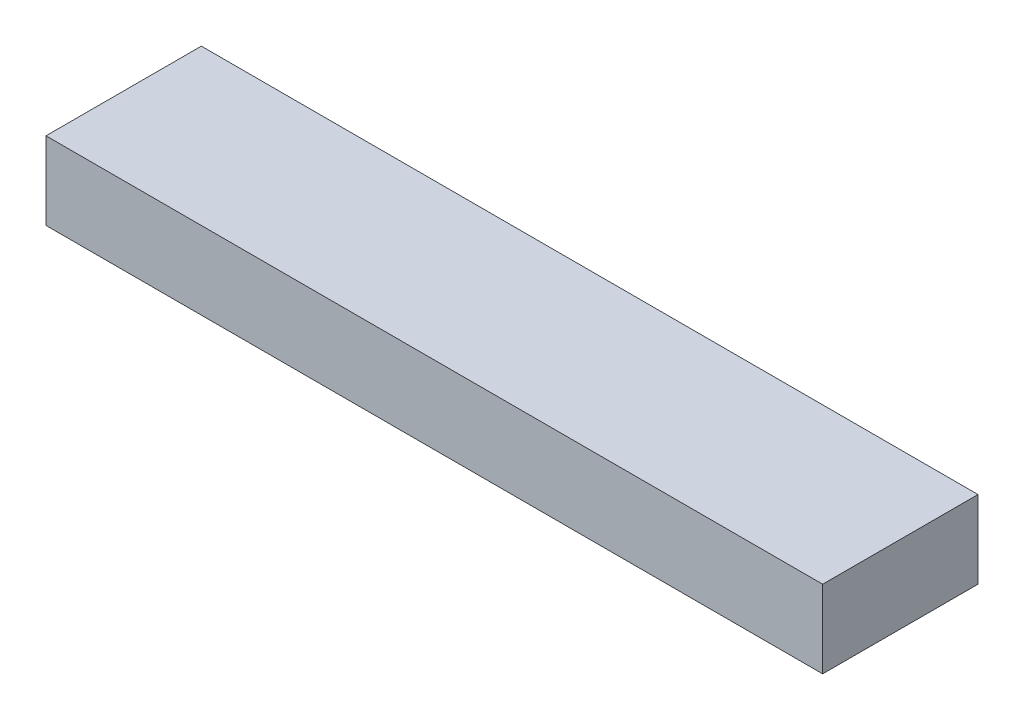
SolidWorks part; units mm, degrees
ref_plane "Front Plane" through (0, 0, 0) normal (0, 0, 1) x (1, 0, 0)
ref_plane "Top Plane" through (0, 0, 0) normal (0, 1, 0) x (1, 0, 0)
ref_plane "Right Plane" through (0, 0, 0) normal (1, 0, 0) x (0, 0, -1)
sketch "Sketch1" plane through (0, 0, 0) normal (0, 1, 0) x (1, 0, 0)
  line L1 (-63.5, 12.7) -> (63.5, 12.7)
  line L2 (-63.5, 12.7) -> (-63.5, -12.7)
  line L3 (-63.5, -12.7) -> (63.5, -12.7)
  line L4 (63.5, 12.7) -> (63.5, -12.7)
  line L5 (-63.5, 12.7) -> (63.5, -12.7) construction
  line L6 (-63.5, -12.7) -> (63.5, 12.7) construction
  point P0 (0, 0)
  dimension "D1" = 127
  dimension "D2" = 25.4
extrude "Boss-Extrude1" add sketch "Sketch1" along normal blind 12.7
